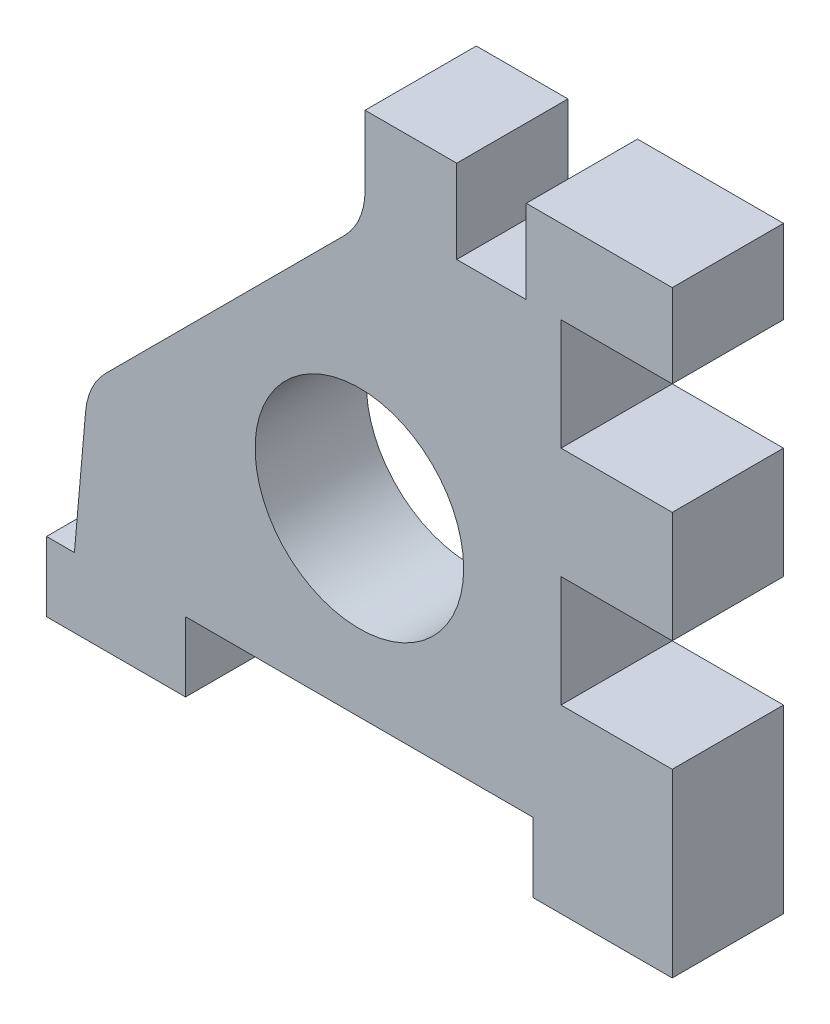
SolidWorks part; units mm, degrees
ref_plane "前视基准面" through (0, 0, 0) normal (0, 0, 1) x (1, 0, 0)
ref_plane "上视基准面" through (0, 0, 0) normal (0, 1, 0) x (1, 0, 0)
ref_plane "右视基准面" through (0, 0, 0) normal (1, 0, 0) x (0, 0, -1)
sketch "草图1" plane through (0, 0, 0) normal (0, 0, 1) x (1, 0, 0)
  line L1 (2.97, 11) -> (22.9088, 30.9388)
  line L2 (45, 0) -> (45, 37.9988)
  line L3 (2.0076, 0) -> (2.97, 11)
  line L4 (45, 0) -> (2.0076, 0)
  line L5 (22.9088, 30.9388) -> (22.9088, 37.9988)
  line L6 (22.9088, 37.9988) -> (45, 37.9988)
  circle A0 centre (22.5, 13) radius 7.5
  dimension "D8" = 15
  dimension "D1" = 2.0076
  dimension "D2" = 85
  dimension "D3" = 20.4924
  dimension "D4" = 140
  dimension "D5" = 42.9924
  dimension "D6" = 7.06
  dimension "D7" = 37.9988
  dimension "D9" = 13
  dimension "D10" = 11
extrude "凸台-拉伸1" add sketch "草图1" along normal blind 8
fillet "圆角1" radius 5 2 edges at (22.9088, 30.9388, 4) (2.97, 11, 4)
sketch "草图2" plane through (0, 0, 8) normal (0, 0, 1) x (1, 0, 0)
  line L0 (32, 37.9988) -> (32, 21.9992) construction
  line L1 (45, 37.9988) -> (22.9088, 37.9988) construction
  line L2 (45, 0) -> (45, 37.9988) construction
  line L3 (29.5, 37.9988) -> (34.5, 37.9988)
  line L4 (29.5, 37.9988) -> (29.5, 31.9988)
  line L5 (29.5, 31.9988) -> (34.5, 31.9988)
  line L6 (34.5, 37.9988) -> (34.5, 31.9988)
  dimension "D1" = 5
  dimension "D2" = 6
  dimension "D3" = 5
  dimension "D4" = 13
extrude "切除-拉伸1" cut sketch "草图2" against normal blind 8
sketch "草图3" plane through (0, 0, 0) normal (0, -1, 0) x (1, 0, 0)
  line L0 (2.0076, 0) -> (45, 0) construction
  line L1 (45, 8) -> (35, 8)
  line L2 (45, 8) -> (45, 0)
  line L3 (45, 0) -> (35, 0)
  line L4 (35, 8) -> (35, 0)
  line L5 (0, 8) -> (10, 8)
  line L6 (0, 8) -> (0, 0)
  line L7 (0, 0) -> (10, 0)
  line L8 (10, 8) -> (10, 0)
  dimension "D1" = 10
  dimension "D2" = 10
extrude "凸台-拉伸2" add sketch "草图3" along normal blind 5
sketch "草图4" plane through (0, 0, 8) normal (0, 0, 1) x (1, 0, 0)
  line L1 (45, 8) -> (37, 8)
  line L2 (45, 8) -> (45, 16)
  line L3 (45, 16) -> (37, 16)
  line L4 (37, 8) -> (37, 16)
  line L5 (45, -5) -> (45, 37.9988) construction
  line L6 (45, 24) -> (37, 24)
  line L7 (45, 24) -> (45, 32)
  line L8 (45, 32) -> (37, 32)
  line L9 (37, 24) -> (37, 32)
  line L10 (10, 0) -> (35, 0) construction
  dimension "D1" = 8
  dimension "D2" = 8
  dimension "D3" = 8
  dimension "D4" = 8
  dimension "D5" = 8
  dimension "D6" = 8
extrude "切除-拉伸2" cut sketch "草图4" against normal through all
